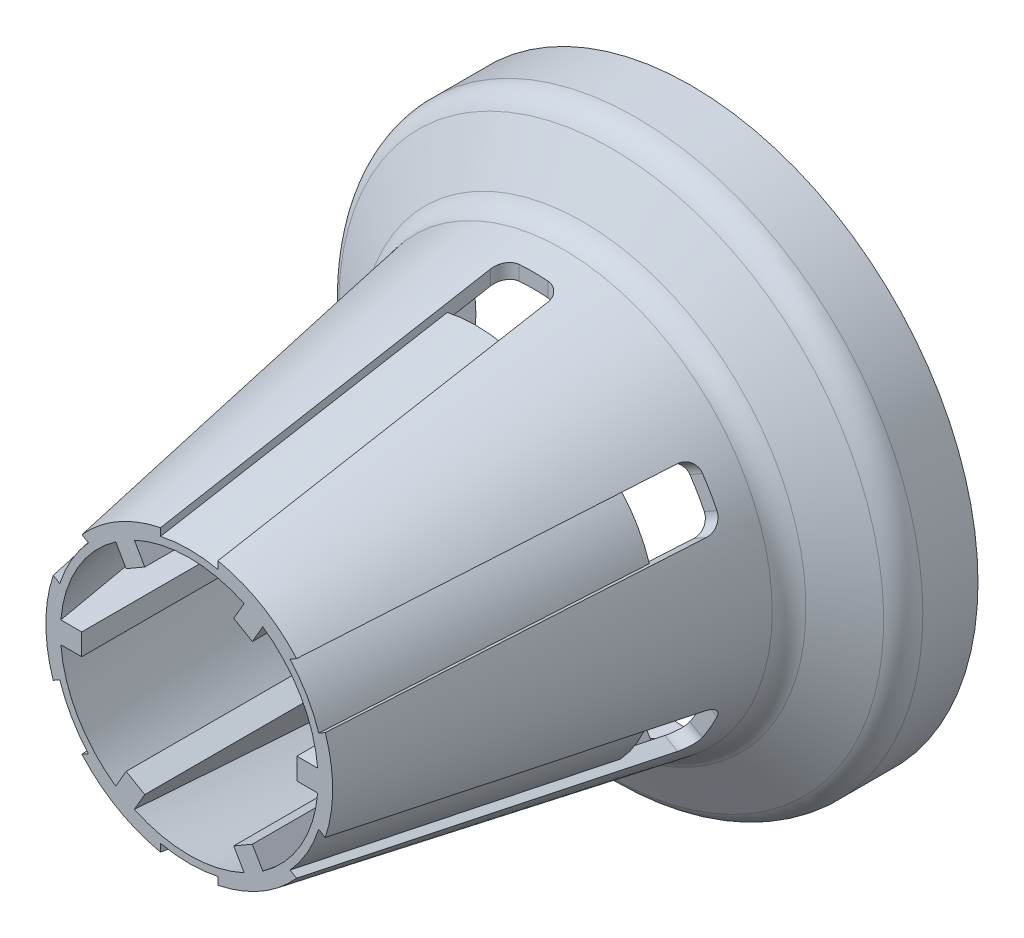
SolidWorks part; units mm, degrees
ref_plane "Płaszczyzna przednia" through (0, 0, 0) normal (0, 0, 1) x (1, 0, 0)
ref_plane "Płaszczyzna górna" through (0, 0, 0) normal (0, 1, 0) x (1, 0, 0)
ref_plane "Płaszczyzna prawa" through (0, 0, 0) normal (1, 0, 0) x (0, 0, -1)
sketch "Szkic1" plane through (0, 0, 0) normal (1, 0, 0) x (0, 0, -1)
  line L0 (-50, 0) -> (20, 0)
  line L1 (20, 0) -> (20, 40)
  line L2 (-50, 20) -> (2.1078, 29.188)
  line L3 (4.8773, 31.1272) -> (8.8453, 38)
  line L4 (-50, 20) -> (-50, 0)
  line L5 (12.3094, 40) -> (20, 40)
  arc A0 (8.8453, 38) -> (12.3094, 40) centre (12.3094, 36) cw
  arc A1 (2.1078, 29.188) -> (4.8773, 31.1272) centre (1.4132, 33.1272) ccw
  point P9 (10, 40)
  dimension "D8" = 4
  dimension "D1" = 20
  dimension "D2" = 40
  dimension "D3" = 70
  dimension "D4" = 10
  dimension "D5" = 30
  dimension "D6" = 10
  dimension "D7" = 50
revolve "Obrót1" add sketch "Szkic1" angle 360 about L0
shell "Skorupa1" thickness 2
sketch "Szkic2" plane through (0, 0, 50) normal (0, 0, 1) x (1, 0, 0)
  line L0 (0, 0) -> (0, 18.9691) construction
  line L1 (-4, 18.5426) -> (-4, 24.5426)
  line L2 (-4, 24.5426) -> (4, 24.5426)
  line L3 (4, 24.5426) -> (4, 18.5426)
  circle A2 centre (0, 0) radius 18.9691
  arc A3 (4, 18.5426) -> (-4, 18.5426) centre (0, 0) ccw
  dimension "D2" = 8
  dimension "D3" = 6
  dimension "D1" = 1
sketch "Szkic3" plane through (0, 0, 0) normal (1, 0, 0) x (0, 0, -1)
  line L0 (-50, 18.9691) -> (-10, 26.0222)
  line L1 (-50, 0) -> (0, 0) construction
  line L2 (-50, 0) -> (-50, 18.9691) construction
  dimension "D1" = 10
  dimension "D2" = 40
sweep "Wycięcie-wyciągnięcie po ścieżce1" cut profiles "Szkic2" path "Szkic3"
sketch "Szkic4" plane through (0, 0, 0) normal (0, 1, 0) x (1, 0, 0)
  line L1 (-2, -2) -> (2, -2)
  line L2 (-4, -4) -> (-4, -10)
  line L3 (-4, -10) -> (4, -10)
  line L4 (4, -4) -> (4, -10)
  line L5 (-4, -2) -> (4, -10) construction
  line L6 (-4, -10) -> (4, -2) construction
  arc A0 (2, -2) -> (4, -4) centre (2, -4) cw
  arc A1 (-2, -2) -> (-4, -4) centre (-2, -4) ccw
  point P0 (0, -6)
  dimension "D4" = 2
  dimension "D1" = 8
  dimension "D2" = 8
  dimension "D3" = 2
extrude "Wytnij-wyciągnięcie1" cut sketch "Szkic4" along normal up to next
pattern_circular "Szyk kołowy1" count 6 over 360 about axis through (0, 0, 50) along (0, 0, -1) of "Wycięcie-wyciągnięcie po ścieżce1", "Wytnij-wyciągnięcie1"
sketch "Szkic5" plane through (0, 0, 50) normal (0, 0, 1) x (1, 0, 0)
  line L0 (0, 0) -> (-10, -17.3205) construction
  line L1 (-10.2523, -14.7574) -> (-8.799, -12.2404)
  line L2 (-8.799, -12.2404) -> (-6.201, -13.7404)
  line L3 (-6.201, -13.7404) -> (-7.6542, -16.2574)
  circle A0 centre (0, 0) radius 17.9691 construction
  arc A1 (-10.2523, -14.7574) -> (-7.6542, -16.2574) centre (0, 0) ccw
  arc A2 (14.9706, 13.2621) -> (4, 19.5959) centre (0, 0) ccw construction
  arc A3 (14.9706, 13.2621) -> (4, 19.5959) centre (0, 0) ccw construction
  dimension "D1" = 3
  dimension "D2" = 15
sketch "Szkic6" plane through (0, 0, 0) normal (0, 0, 1) x (1, 0, 0)
  line L0 (-8.799, -12.2404) -> (-6.201, -13.7404) construction
  line L1 (-8.799, -12.2404) -> (-6.201, -13.7404)
  line L2 (-6.201, -13.7404) -> (-12.2895, -24.286)
  line L3 (-8.799, -12.2404) -> (-14.8876, -22.786)
  circle A1 centre (0, 0) radius 27.2184
  arc A2 (-14.8876, -22.786) -> (-12.2895, -24.286) centre (0, 0) ccw
  dimension "D1" = 0
loft "Wyciągnięcie po profilach1" add profiles "Szkic5", "Szkic6"
fillet "Zaokrąglenie1" radius 10 1 edges
pattern_circular "Szyk kołowy2" count 6 over 360 about axis through (0, 0, 0) along (0, 0, 1) of "Zaokrąglenie1", "Wyciągnięcie po profilach1"
